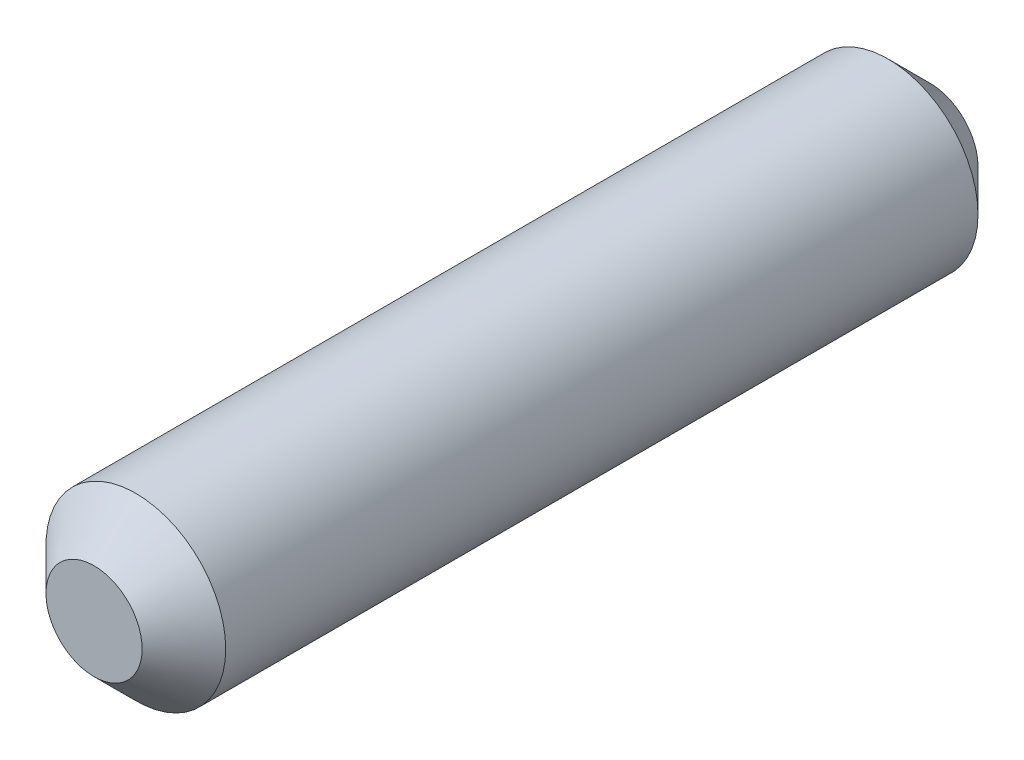
SolidWorks part; units mm, degrees
ref_plane "Front Plane" through (0, 0, 0) normal (0, 0, 1) x (1, 0, 0)
ref_plane "Top Plane" through (0, 0, 0) normal (0, 1, 0) x (1, 0, 0)
ref_plane "Right Plane" through (0, 0, 0) normal (1, 0, 0) x (0, 0, -1)
sketch "Sketch1" plane through (0, 0, 0) normal (0, 0, 1) x (1, 0, 0)
  circle A0 centre (0, 0) radius 1.075
  dimension "D1" = 2.15
extrude "Boss-Extrude1" add sketch "Sketch1" along normal blind 10
chamfer "Chamfer1" distance 0.5 angle 45 2 edges at (1.075, 0, 0) (1.075, 0, 10)
